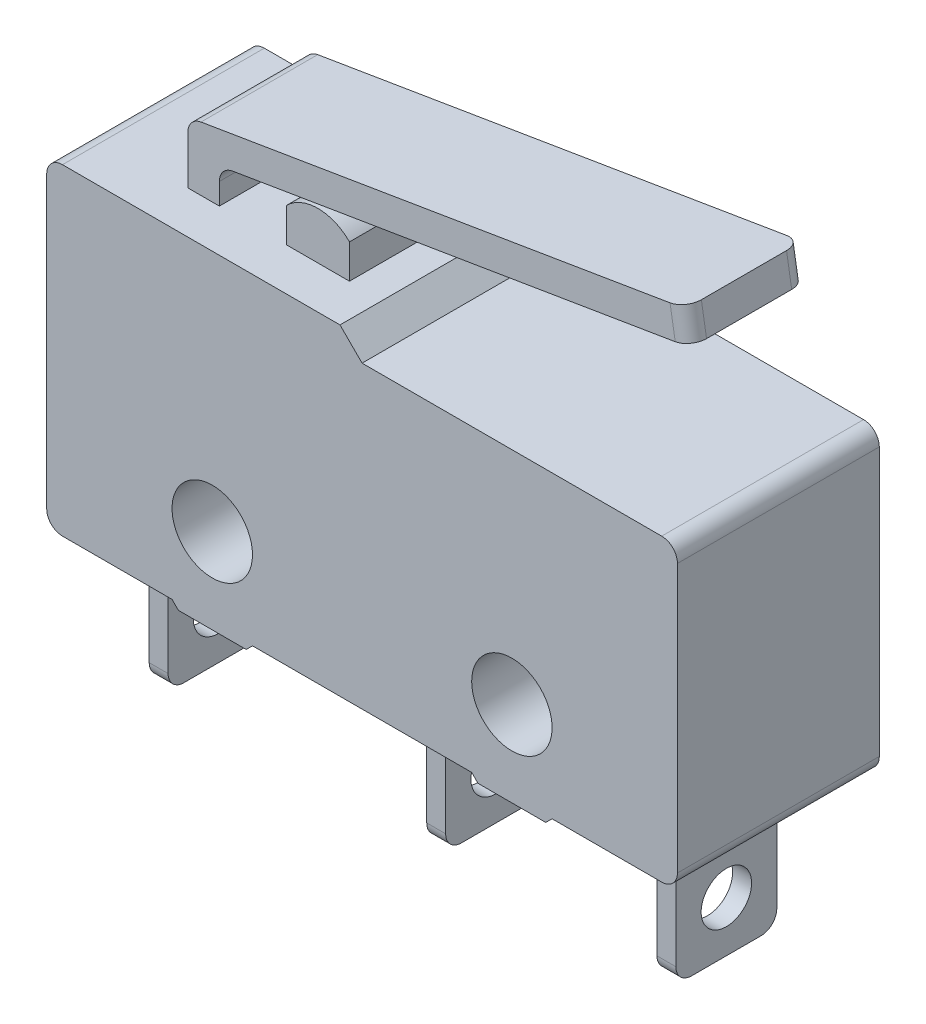
SolidWorks part; units mm, degrees
ref_plane "前视基准面" through (0, 0, 0) normal (0, 0, 1) x (1, 0, 0)
ref_plane "上视基准面" through (0, 0, 0) normal (0, 1, 0) x (1, 0, 0)
ref_plane "右视基准面" through (0, 0, 0) normal (1, 0, 0) x (0, 0, -1)
other "Configuration Table"
sketch "草图1" plane through (0, 0, 0) normal (0, 0, 1) x (1, 0, 0)
  line L0 (0, 0) -> (-50000, 0) construction
  line L1 (0, 0) -> (0, -50000) construction
  line L2 (-10, -4.75) -> (-10, 4.75)
  line L3 (0, 4.75) -> (10, 4.75)
  line L4 (10, 4.75) -> (10, -4.75)
  line L5 (-10, -4.75) -> (-6.025, -4.75)
  line L6 (-10, 4.75) -> (-10, 4.95)
  line L7 (-9.5, 5.45) -> (-0.7, 5.45)
  line L8 (-0.7, 5.45) -> (0, 4.75)
  line L9 (-6.025, -2.25) -> (-6.025, -50002.25) construction
  line L10 (-3.475, -2.25) -> (-3.475, -50002.25) construction
  line L11 (-6.025, -4.75) -> (-5.825, -4.95)
  line L12 (-5.825, -4.95) -> (-3.675, -4.95)
  line L13 (-3.675, -4.95) -> (-3.475, -4.75)
  line L14 (3.675, -4.95) -> (3.475, -4.75)
  line L15 (6.025, -4.75) -> (5.825, -4.95)
  line L16 (5.825, -4.95) -> (3.675, -4.95)
  line L17 (-3.475, -4.75) -> (3.475, -4.75)
  line L18 (6.025, -4.75) -> (10, -4.75)
  circle A0 centre (-4.75, -2.25) radius 1.275
  circle A1 centre (4.75, -2.25) radius 1.275
  arc A2 (-10, 4.95) -> (-9.5, 5.45) centre (-9.5, 4.95) cw
  point P10 (10, 0)
  point P11 (-10, 0)
  dimension "D6" = 2.55
  dimension "D8" = 0.5
  dimension "D1" = 20
  dimension "D2" = 9.5
  dimension "D3" = 45
  dimension "D4" = 0.7
  dimension "D5" = 2.5
  dimension "D7" = 9.5
  dimension "D9" = 45
  dimension "D10" = 45
  dimension "D11" = 0.2
extrude "凸台-拉伸1" add sketch "草图1" along normal blind 6.4
fillet "圆角1" radius 0.5 3 edges at (10, 4.75, 3.2) (10, -4.75, 3.2) (-10, -4.75, 3.2)
ref_plane "基准面1" through (0, 0, 3.2) normal (0, 0, 1) x (1, 0, 0)
sketch "草图2" plane through (0, 0, 3.2) normal (0, 0, 1) x (1, 0, 0)
  line L0 (-8.35, -4.75) -> (-8.35, -8.95)
  line L1 (-9.5, -4.75) -> (-6.025, -4.75) construction
  line L2 (-8.35, -8.95) -> (-7.75, -8.95)
  line L3 (-7.75, -8.95) -> (-7.75, -4.75)
  line L4 (-7.75, -4.75) -> (-8.35, -4.75)
  line L5 (0.45, -4.75) -> (0.45, -8.95)
  line L6 (-3.475, -4.75) -> (3.475, -4.75) construction
  line L7 (0.45, -8.95) -> (1.05, -8.95)
  line L8 (1.05, -8.95) -> (1.05, -4.75)
  line L9 (1.05, -4.75) -> (0.45, -4.75)
  line L10 (7.75, -4.75) -> (7.75, -8.95)
  line L11 (6.025, -4.75) -> (9.5, -4.75) construction
  line L12 (7.75, -8.95) -> (8.35, -8.95)
  line L13 (8.35, -8.95) -> (8.35, -4.75)
  line L14 (8.35, -4.75) -> (7.75, -4.75)
  line L15 (-10, 4.95) -> (-10, -4.25) construction
  point P20 (-0.2191, -10.9457)
  dimension "D1" = 4.2
  dimension "D2" = 0.6
  dimension "D3" = 4.2
  dimension "D4" = 4.2
  dimension "D5" = 0.6
  dimension "D6" = 0.6
  dimension "D7" = 1.65
  dimension "D8" = 8.8
  dimension "D9" = 7.3
extrude "凸台-拉伸2" add sketch "草图2" along normal blind 1.6 and the other way blind 1.6
sketch "草图3" plane through (0, 0, 3.2) normal (0, 0, 1) x (1, 0, 0)
  line L0 (-3.75, 5.45) -> (-3.75, 6.5298)
  line L1 (-0.7, 5.45) -> (-9.5, 5.45) construction
  line L2 (-1.75, 6.5298) -> (-1.75, 5.45)
  line L3 (-1.75, 5.45) -> (-3.75, 5.45)
  line L4 (-6.7525, -4.75) -> (-50006.7525, -4.75) construction
  line L6 (-4.75, -4.95) -> (-4.75, -50004.95) construction
  line L7 (-5.825, -4.95) -> (-3.675, -4.95) construction
  line L8 (-4.75, -2.25) -> (-50004.75, -2.25) construction
  line L9 (-2.75, 5.45) -> (-2.75, -49994.55) construction
  line L10 (4.75, -4.95) -> (4.75, 49995.05) construction
  line L11 (3.675, -4.95) -> (5.825, -4.95) construction
  arc A1 (-4.75, 13.745) -> (-2.75, 14.2475) centre (-2.75, 10.0156) cw
  arc A2 (-3.75, 6.5298) -> (-1.75, 6.5298) centre (-2.75, 5.55) cw
  point P13 (-4.75, -4.95)
  point P19 (-2.75, 5.45)
  point P24 (4.75, -4.95)
  point P25 (-2.75, 6.95)
  dimension "D3" = 1.4
  dimension "D1" = 7.5
  dimension "D2" = 2
  dimension "D4" = 9.2
extrude "凸台-拉伸3" add sketch "草图3" along normal blind 1.85 and the other way blind 1.85 contours A2 L0 L3 L2
sketch "草图4" plane through (0, 0, 3.2) normal (0, 0, 1) x (1, 0, 0)
  line L0 (-10, 4.6629) -> (-10, 50004.6629) construction
  line L1 (-10, 4.95) -> (-10, -4.25) construction
  line L2 (-2.75, 6.95) -> (-2.75, -49993.05) construction
  line L3 (-10, 3.1671) -> (-2.75, 3.1671) construction
  line L4 (-6.375, 5.9837) -> (-6.375, -49994.0163) construction
  line L5 (-6.875, 7.3989) -> (-6.875, 5.45)
  line L7 (-0.7, 5.45) -> (-9.5, 5.45) construction
  line L9 (-5.875, 5.45) -> (-5.875, 6.45)
  line L11 (-6.875, 7.3989) -> (-2.7969, 8.0765)
  line L12 (-2.7969, 8.0765) -> (8.9086, 10.0212)
  line L14 (9.0889, 8.9361) -> (8.9086, 10.0212)
  line L15 (-6.875, 5.45) -> (-6.875, 4.3953)
  line L16 (-6.875, 4.3953) -> (-5.875, 4.3953)
  line L17 (-5.875, 4.3953) -> (-5.875, 5.45)
  line L18 (-5.875, 6.45) -> (-5.875, 6.5514)
  line L19 (-5.875, 6.5514) -> (9.0725, 9.0348)
  arc A0 (-1.75, 6.5298) -> (-3.75, 6.5298) centre (-2.75, 5.55) ccw construction
  point P7 (-2.75, 6.95)
  point P20 (-6.375, 3.1671)
  dimension "D1" = 1
  dimension "D3" = 1
  dimension "D4" = 16
extrude "凸台-拉伸7" add sketch "草图4" along normal blind 1.85 and the other way blind 1.85 contours L18 L19 L14 L12 L11 L5 L15 L16 L17 L9
fillet "圆角2" radius 0.5 4 edges at (-5.875, 6.5514, 3.2) (-6.875, 7.3989, 3.2) (8.9906, 9.528, 1.35) (8.9906, 9.528, 5.05)
fillet "圆角3" radius 0.5 6 edges at (8.05, -8.95, 4.8) (0.75, -8.95, 4.8) (-8.05, -8.95, 4.8) (-8.05, -8.95, 1.6) (0.75, -8.95, 1.6) (8.05, -8.95, 1.6)
sketch "草图5" plane through (0, 0, 0) normal (1, 0, 0) x (0, 0, -1)
  line L0 (-3.2, -8.95) -> (-3.2, -50008.95) construction
  line L1 (-2.1, -8.95) -> (-4.3, -8.95) construction
  circle A0 centre (-3.2, -7.35) radius 0.8
  point P4 (-3.2, -8.95)
  dimension "D1" = 1.6
  dimension "D2" = 1.6
extrude "切除-拉伸1" cut sketch "草图5" against normal through all and the other way through all
